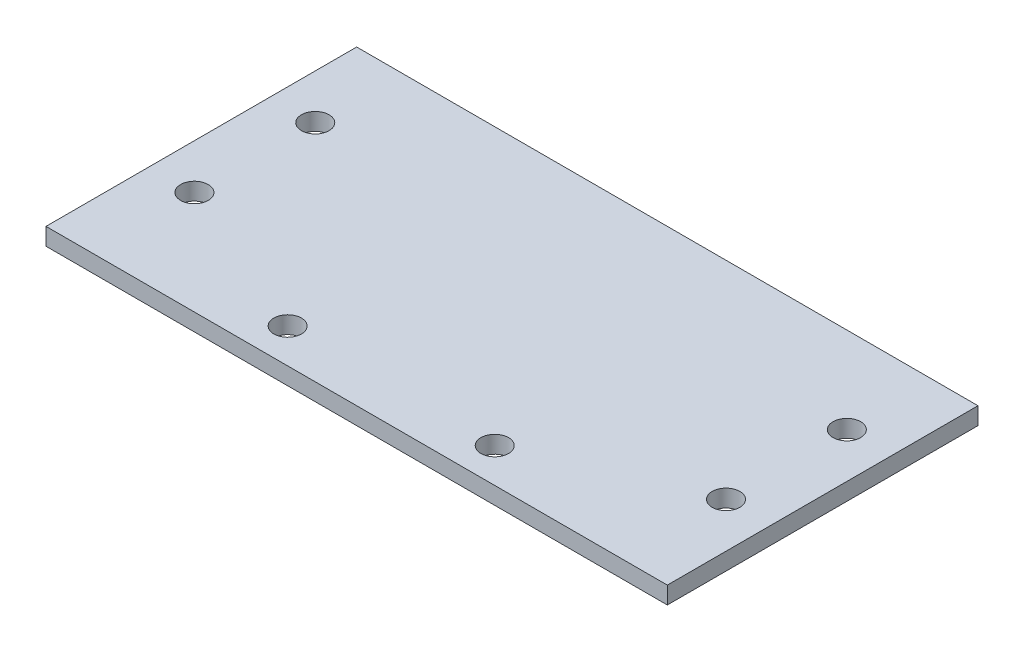
SolidWorks part; units mm, degrees
material "ABS PC"
ref_plane "Front Plane" through (0, 0, 0) normal (0, 0, 1) x (1, 0, 0)
ref_plane "Top Plane" through (0, 0, 0) normal (0, 1, 0) x (1, 0, 0)
ref_plane "Right Plane" through (0, 0, 0) normal (1, 0, 0) x (0, 0, -1)
sketch "Sketch1" plane through (0, 0, 0) normal (0, 1, 0) x (1, 0, 0)
  line L0 (0, -45) -> (0, 45) construction
  line L1 (-90, -45) -> (90, -45)
  line L2 (-90, -45) -> (-90, 45)
  line L3 (-90, 45) -> (90, 45)
  line L4 (90, -45) -> (90, 45)
  line L5 (-90, -45) -> (90, 45) construction
  line L6 (-90, 45) -> (90, -45) construction
  circle A0 centre (-77, 20) radius 4
  circle A1 centre (-77, -15) radius 4
  circle A2 centre (-30, -35) radius 4
  circle A3 centre (30, -35) radius 4
  circle A4 centre (77, 20) radius 4
  circle A5 centre (77, -15) radius 4
  point P0 (0, 0)
  point P20 (0, 0)
  point P21 (-77, -15)
  point P22 (-30, -32.101)
  dimension "D7" = 8
  dimension "D1" = 90
  dimension "D2" = 180
  dimension "D3" = 35
  dimension "D4" = 30
  dimension "D5" = 13
  dimension "D6" = 47
  dimension "D8" = 10
extrude "Boss-Extrude1" add sketch "Sketch1" along normal mid plane 5
